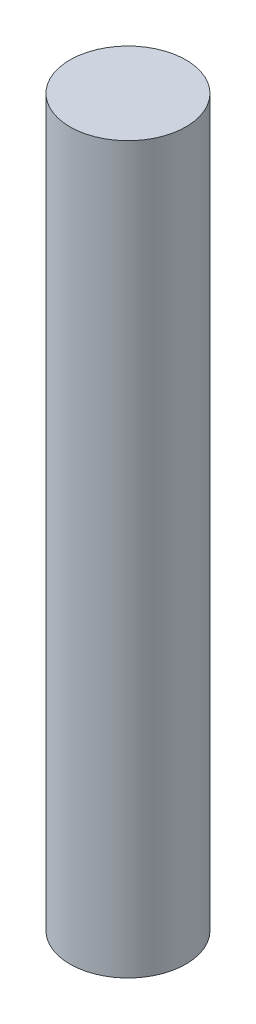
SolidWorks part; units mm, degrees
ref_plane "前视基准面" through (0, 0, 0) normal (0, 0, 1) x (1, 0, 0)
ref_plane "上视基准面" through (0, 0, 0) normal (0, 1, 0) x (1, 0, 0)
ref_plane "右视基准面" through (0, 0, 0) normal (1, 0, 0) x (0, 0, -1)
other "Configuration Table"
sketch "草图1" plane through (0, 0, 0) normal (0, 1, 0) x (1, 0, 0)
  circle A0 centre (0, 0) radius 12
  dimension "D1" = 24
extrude "凸台-拉伸1" add sketch "草图1" along normal blind 150
